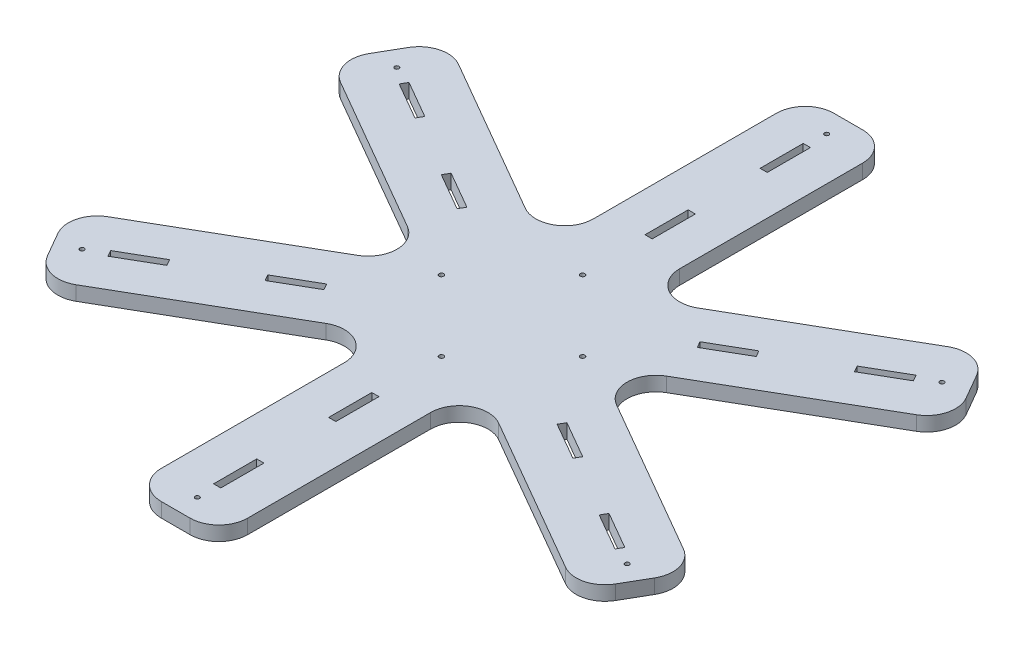
SolidWorks part; units mm, degrees
ref_plane "前视基准面" through (0, 0, 0) normal (0, 0, 1) x (1, 0, 0)
ref_plane "上视基准面" through (0, 0, 0) normal (0, 1, 0) x (1, 0, 0)
ref_plane "右视基准面" through (0, 0, 0) normal (1, 0, 0) x (0, 0, -1)
other "Configuration Table"
sketch "草图2" plane through (0, 0, 0) normal (0, 1, 0) x (1, 0, 0)
  line L1 (-23, -23) -> (23, -23)
  line L2 (-23, -23) -> (-23, 23)
  line L3 (-23, 23) -> (23, 23)
  line L4 (23, -23) -> (23, 23)
  line L5 (-23, -23) -> (23, 23) construction
  line L6 (-23, 23) -> (23, -23) construction
extrude "凸台-拉伸1" add sketch "草图2" along normal blind 10
sketch "草图4" plane through (0, 10, 0) normal (0, 1, 0) x (1, 0, 0)
  circle A1 centre (-49.1, 0) radius 1.6
  circle A2 centre (0, -49.1) radius 1.6
  circle A3 centre (49.1, 0) radius 1.6
  circle A4 centre (0, 49.1) radius 1.6
  circle A5 centre (0, 0) radius 55
extrude "凸台-拉伸2" add sketch "草图4" against normal blind 10
sketch "草图5" plane through (0, 10, 0) normal (0, 1, 0) x (1, 0, 0)
  line L20 (30, -233.8269) -> (30, -51.9615)
  line L23 (-187.5, -142.8942) -> (-217.5, -90.9327)
  line L24 (-187.5, -142.8942) -> (-30, -51.9615)
  line L25 (-217.5, -90.9327) -> (-60, 0)
  line L27 (-217.5, 90.9327) -> (-187.5, 142.8942)
  line L31 (-30, 233.8269) -> (30, 233.8269)
  line L32 (-30, 233.8269) -> (-30, 51.9615)
  line L33 (30, 233.8269) -> (30, 51.9615)
  line L35 (-217.5, 90.9327) -> (-60, 0)
  line L36 (-187.5, 142.8942) -> (-30, 51.9615)
  line L37 (187.5, 142.8942) -> (30, 51.9615)
  line L38 (217.5, 90.9327) -> (60, 0)
  line L39 (187.5, -142.8942) -> (30, -51.9615)
  line L40 (-30, -233.8269) -> (-30, -51.9615)
  line L41 (217.5, -90.9327) -> (187.5, -142.8942)
  line L42 (187.5, 142.8942) -> (217.5, 90.9327)
  line L43 (217.5, -90.9327) -> (60, 0)
  line L44 (-30, -233.8269) -> (30, -233.8269)
  circle A2 centre (0, 0) radius 55
  point P16 (-202.5, 116.9134)
  point P21 (-202.5, -116.9134)
  point P26 (0, 233.8269)
  point P27 (0, -233.8269)
  point P30 (202.5, -116.9134)
  point P44 (0, 233.8269)
  point P50 (202.5, -116.9134)
  point P53 (0, -233.8269)
extrude "凸台-拉伸3" add sketch "草图5" against normal blind 10
sketch "草图6" plane through (0, 10, 0) normal (0, 1, 0) x (1, 0, 0)
  line L0 (152.8044, 85.3349) -> (150.3044, 89.6651)
  line L1 (-2.5, 205) -> (2.5, 205)
  line L2 (-2.5, 205) -> (-2.5, 175)
  line L3 (-2.5, 175) -> (2.5, 175)
  line L4 (2.5, 205) -> (2.5, 175)
  line L5 (-2.5, 205) -> (2.5, 175) construction
  line L6 (-2.5, 175) -> (2.5, 205) construction
  line L7 (-2.5, 125) -> (2.5, 125)
  line L8 (-2.5, 125) -> (-2.5, 95)
  line L9 (-2.5, 95) -> (2.5, 95)
  line L10 (2.5, 125) -> (2.5, 95)
  line L11 (-2.5, 125) -> (2.5, 95) construction
  line L12 (-2.5, 95) -> (2.5, 125) construction
  line L13 (83.5224, 45.3349) -> (81.0224, 49.6651)
  line L14 (-107.0032, -64.6651) -> (-109.5032, -60.3349)
  line L15 (81.0224, -49.6651) -> (83.5224, -45.3349)
  line L16 (152.8044, 85.3349) -> (178.7852, 100.3349)
  line L17 (150.3044, 89.6651) -> (176.2852, 104.6651)
  line L18 (178.7852, 100.3349) -> (176.2852, 104.6651)
  line L19 (152.8044, 85.3349) -> (176.2852, 104.6651) construction
  line L20 (150.3044, 89.6651) -> (178.7852, 100.3349) construction
  line L21 (83.5224, 45.3349) -> (109.5032, 60.3349)
  line L22 (81.0224, 49.6651) -> (107.0032, 64.6651)
  line L23 (109.5032, 60.3349) -> (107.0032, 64.6651)
  line L24 (83.5224, 45.3349) -> (107.0032, 64.6651) construction
  line L25 (81.0224, 49.6651) -> (109.5032, 60.3349) construction
  line L27 (-109.5032, 60.3349) -> (-107.0032, 64.6651)
  line L28 (-107.0032, -64.6651) -> (-81.0224, -49.6651)
  line L29 (-109.5032, -60.3349) -> (-83.5224, -45.3349)
  line L30 (-81.0224, -49.6651) -> (-83.5224, -45.3349)
  line L31 (-107.0032, -64.6651) -> (-83.5224, -45.3349) construction
  line L32 (-109.5032, -60.3349) -> (-81.0224, -49.6651) construction
  line L33 (-176.2852, -104.6651) -> (-178.7852, -100.3349)
  line L34 (-176.2852, -104.6651) -> (-150.3044, -89.6651)
  line L35 (-178.7852, -100.3349) -> (-152.8044, -85.3349)
  line L36 (-150.3044, -89.6651) -> (-152.8044, -85.3349)
  line L37 (-176.2852, -104.6651) -> (-152.8044, -85.3349) construction
  line L38 (-178.7852, -100.3349) -> (-150.3044, -89.6651) construction
  line L40 (-109.5032, 60.3349) -> (-83.5224, 45.3349)
  line L41 (81.0224, -49.6651) -> (107.0032, -64.6651)
  line L42 (83.5224, -45.3349) -> (109.5032, -60.3349)
  line L43 (107.0032, -64.6651) -> (109.5032, -60.3349)
  line L44 (81.0224, -49.6651) -> (109.5032, -60.3349) construction
  line L45 (83.5224, -45.3349) -> (107.0032, -64.6651) construction
  line L46 (150.3044, -89.6651) -> (152.8044, -85.3349)
  line L50 (150.3044, -89.6651) -> (176.2852, -104.6651)
  line L51 (152.8044, -85.3349) -> (178.7852, -100.3349)
  line L52 (176.2852, -104.6651) -> (178.7852, -100.3349)
  line L53 (150.3044, -89.6651) -> (178.7852, -100.3349) construction
  line L54 (152.8044, -85.3349) -> (176.2852, -104.6651) construction
  line L55 (-107.0032, 64.6651) -> (-81.0224, 49.6651)
  line L56 (-83.5224, 45.3349) -> (-81.0224, 49.6651)
  line L57 (-109.5032, 60.3349) -> (-81.0224, 49.6651) construction
  line L58 (-107.0032, 64.6651) -> (-83.5224, 45.3349) construction
  line L59 (-178.7852, 100.3349) -> (-176.2852, 104.6651)
  line L60 (-178.7852, 100.3349) -> (-152.8044, 85.3349)
  line L61 (-176.2852, 104.6651) -> (-150.3044, 89.6651)
  line L62 (-152.8044, 85.3349) -> (-150.3044, 89.6651)
  line L63 (-178.7852, 100.3349) -> (-150.3044, 89.6651) construction
  line L64 (-176.2852, 104.6651) -> (-152.8044, 85.3349) construction
  line L65 (-2.5, -95) -> (2.5, -95)
  line L66 (-2.5, -95) -> (-2.5, -125)
  line L67 (-2.5, -125) -> (2.5, -125)
  line L68 (2.5, -95) -> (2.5, -125)
  line L69 (-2.5, -95) -> (2.5, -125) construction
  line L70 (-2.5, -125) -> (2.5, -95) construction
  line L71 (-2.5, -175) -> (2.5, -175)
  line L72 (-2.5, -175) -> (-2.5, -205)
  line L73 (-2.5, -205) -> (2.5, -205)
  line L74 (2.5, -175) -> (2.5, -205)
  line L75 (-2.5, -175) -> (2.5, -205) construction
  line L76 (-2.5, -205) -> (2.5, -175) construction
  circle A0 centre (0, 218.8269) radius 1.5
  circle A1 centre (189.5096, 109.4134) radius 1.5
  circle A2 centre (189.5096, -109.4134) radius 1.5
  circle A4 centre (0, -218.8269) radius 1.5
  circle A5 centre (-189.5096, -109.4134) radius 1.5
  circle A6 centre (-189.5096, 109.4134) radius 1.5
  point P0 (0, 190)
  point P5 (0, 110)
  point P11 (0, -110)
  point P57 (0, -190)
extrude "切除-拉伸1" cut sketch "草图6" against normal through all
fillet "圆角1" radius 20 18 edges at (-30, 5, 51.9615) (-187.5, 5, 142.8942) (-217.5, 5, 90.9327) (-60, 5, 0) (-217.5, 5, -90.9327) (-187.5, 5, -142.8942) (-30, 5, -51.9615) (-30, 5, -233.8269) (30, 5, -233.8269) (30, 5, -51.9615) (187.5, 5, -142.8942) (217.5, 5, -90.9327) (60, 5, 0) (217.5, 5, 90.9327) (187.5, 5, 142.8942) (30, 5, 51.9615) (-30, 5, 233.8269) (30, 5, 233.8269)
